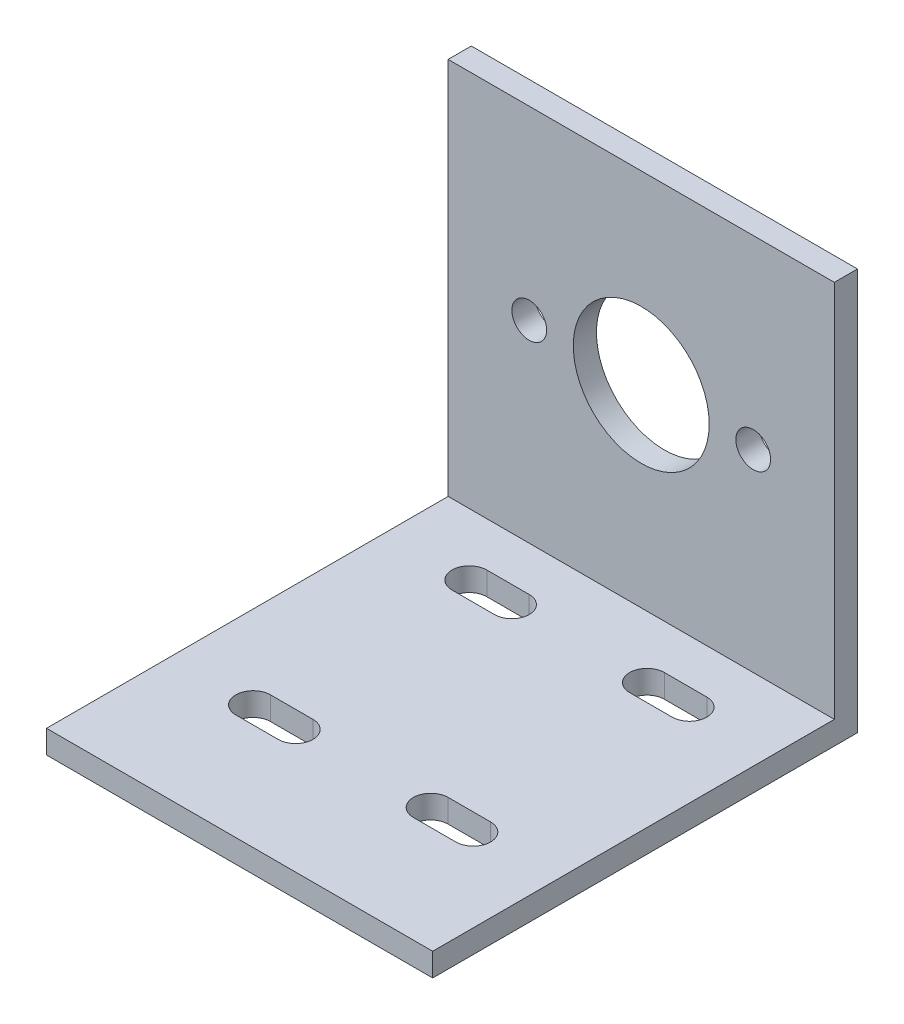
SolidWorks part; units mm, degrees
material "AISI 1035 Stahl"
ref_plane "Ebene vorne" through (0, 0, 0) normal (0, 0, 1) x (1, 0, 0)
ref_plane "Ebene oben" through (0, 0, 0) normal (0, 1, 0) x (1, 0, 0)
ref_plane "Ebene rechts" through (0, 0, 0) normal (1, 0, 0) x (0, 0, -1)
sketch "Skizze1" plane through (0, 0, 0) normal (0, 0, 1) x (1, 0, 0)
  line L1 (-25, -26) -> (25, -26)
  line L2 (-25, -26) -> (-25, 26)
  line L3 (-25, 26) -> (25, 26)
  line L4 (25, -26) -> (25, 26)
  line L5 (-25, -26) -> (25, 26) construction
  line L6 (-25, 26) -> (25, -26) construction
  circle A3 centre (0, 2) radius 8.8
  circle A4 centre (-14.5, 2) radius 2.25
  circle A5 centre (14.5, 2) radius 2.25
  point P0 (0, 0)
  dimension "D3" = 17.6
  dimension "D4" = 4.5
  dimension "D5" = 29
  dimension "D1" = 50
  dimension "D2" = 52
  dimension "D6" = 14.5
  dimension "D7" = 24
extrude "Aufsatz-Linear austragen1" add sketch "Skizze1" along normal blind 3
sketch "Skizze2" plane through (0, 0, 3) normal (0, 0, 1) x (1, 0, 0)
  line L0 (25, -26) -> (25, 26) construction
  line L1 (-25, -26) -> (25, -26)
  line L2 (-25, -26) -> (-25, -23.0002)
  line L3 (-25, -23.0002) -> (25, -23.0002)
  line L4 (25, -26) -> (25, -23.0002)
extrude "Aufsatz-Linear austragen2" add sketch "Skizze2" along normal blind 52
sketch "Skizze3" plane through (0, -23.0002, 0) normal (0, 1, 0) x (1, 0, 0)
  line L0 (-14.25, -39) -> (-8.75, -39) construction
  line L1 (-14.25, -36.75) -> (-8.75, -36.75)
  line L2 (-14.25, -41.25) -> (-8.75, -41.25)
  line L3 (8.75, -39) -> (14.25, -39) construction
  line L4 (8.75, -36.75) -> (14.25, -36.75)
  line L5 (8.75, -41.25) -> (14.25, -41.25)
  line L6 (-25, -55) -> (-25, -3) construction
  line L8 (-14.25, -11) -> (-8.75, -11) construction
  line L9 (-14.25, -8.75) -> (-8.75, -8.75)
  line L10 (-14.25, -13.25) -> (-8.75, -13.25)
  line L11 (8.75, -11) -> (14.25, -11) construction
  line L12 (8.75, -8.75) -> (14.25, -8.75)
  line L13 (8.75, -13.25) -> (14.25, -13.25)
  line L14 (25, -55) -> (25, -3) construction
  arc A0 (-14.25, -36.75) -> (-14.25, -41.25) centre (-14.25, -39) ccw
  arc A1 (-8.75, -41.25) -> (-8.75, -36.75) centre (-8.75, -39) ccw
  arc A2 (8.75, -36.75) -> (8.75, -41.25) centre (8.75, -39) ccw
  arc A3 (14.25, -41.25) -> (14.25, -36.75) centre (14.25, -39) ccw
  arc A4 (-14.25, -8.75) -> (-14.25, -13.25) centre (-14.25, -11) ccw
  arc A5 (-8.75, -13.25) -> (-8.75, -8.75) centre (-8.75, -11) ccw
  arc A6 (8.75, -8.75) -> (8.75, -13.25) centre (8.75, -11) ccw
  arc A7 (14.25, -13.25) -> (14.25, -8.75) centre (14.25, -11) ccw
  point P2 (-11.5, -39)
  point P7 (11.5, -39)
  point P16 (-6.5, -39)
  point P17 (-16.5, -39)
  point P20 (-11.5, -11)
  point P27 (11.5, -11)
  point P32 (0, 0)
  dimension "D1" = 23
  dimension "D2" = 13.5
  dimension "D3" = 11
  dimension "D4" = 4.5
  dimension "D5" = 10
  dimension "D6" = 28
  dimension "D7" = 28
  dimension "D8" = 23
  dimension "D9" = 13.5
extrude "Schnitt-Linear austragen1" cut sketch "Skizze3" against normal through all
